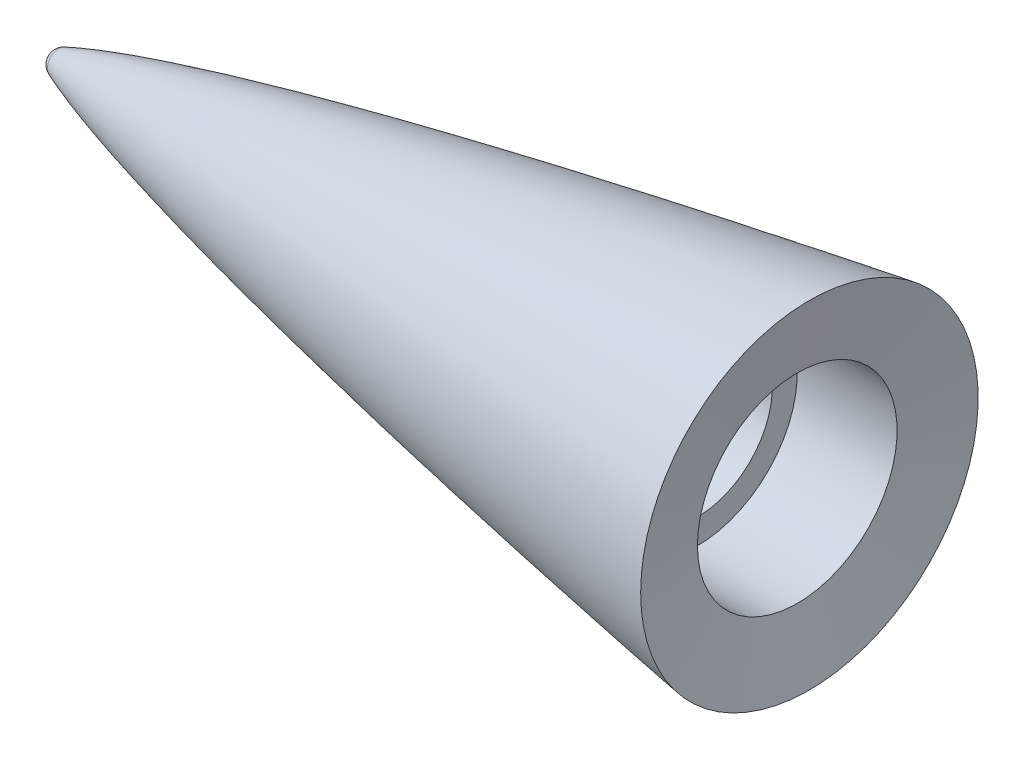
SolidWorks part; units mm, degrees
material "6061-T6 (SS)"
ref_plane "Front Plane" through (0, 0, 0) normal (0, 0, 1) x (1, 0, 0)
ref_plane "Top Plane" through (0, 0, 0) normal (0, 1, 0) x (1, 0, 0)
ref_plane "Right Plane" through (0, 0, 0) normal (1, 0, 0) x (0, 0, -1)
sketch "Sketch1" plane through (0, 0, 0) normal (0, 1, 0) x (1, 0, 0)
  line L0 (0, 0) -> (113.3431, 0) construction
  line L1 (1.6973, 0) -> (45.8194, 0)
  line L2 (83.9194, 12.7) -> (96.6194, 12.7)
  line L3 (96.6194, 12.7) -> (98.1654, 21.4679)
  line L4 (83.9194, 9.525) -> (58.5194, 9.525)
  line L5 (83.9194, 12.7) -> (82.8669, 18.9622) construction
  line L6 (58.5194, 9.525) -> (45.8194, 0)
  line L8 (83.9194, 12.7) -> (83.9194, 9.525)
  arc A0 (2.6821, 1.4686) -> (1.6973, 0) centre (3.2848, 0) ccw
  spline S0 degree 4 poles (0, 0) (0.0034, 0.0099) (0.0124, 0.0287) (0.036, 0.0594) (0.0734, 0.1004) (0.1241, 0.1478) (0.1961, 0.208) (0.3018, 0.2875) (0.4718, 0.4021) (0.7529, 0.5714) (1.2295, 0.826) (2.0659, 1.2203) (3.5324, 1.8251) (5.9654, 2.7008) (9.9595, 3.9615) (15.3529, 5.459) (21.8477, 7.0868) (29.0559, 8.7493) (36.2876, 10.3139) (43.5327, 11.8013) (50.7947, 13.2272) (58.0593, 14.5995) (64.4352, 15.7629) (69.8852, 16.7323) (74.4605, 17.5301) (78.0669, 18.1509) (81.7865, 18.7815) (85.3087, 19.3727) (89.1704, 20.0106) (92.4601, 20.5499) (97.1008, 21.2989) (100.2743, 21.8052) (104.805, 22.5216) (106.4979, 22.7829) (108.0668, 23.0282) knots 0 0 0 0 0 0.000378 0.000756 0.001385 0.00201 0.00288 0.004147 0.006163 0.009417 0.014733 0.02367 0.039565 0.066726 0.108156 0.174994 0.241832 0.30867 0.375509 0.442347 0.509185 0.576023 0.642862 0.676281 0.7097 0.743119 0.776538 0.809957 0.843376 0.876795 0.910214 0.955107 1 1 1 1 1 construction
  spline S1 degree 4 poles (2.6821, 1.4686) (2.9821, 1.5917) (3.9828, 1.987) (6.0755, 2.7356) (9.9593, 3.9614) (15.3526, 5.4589) (21.8473, 7.0867) (29.0554, 8.7492) (36.2869, 10.3137) (43.5319, 11.8011) (50.7938, 13.227) (58.0582, 14.5993) (64.434, 15.7626) (69.8839, 16.7321) (74.4591, 17.5298) (78.0654, 18.1507) (81.785, 18.7813) (85.3071, 19.3724) (89.1687, 20.0104) (92.4584, 20.5496) (95.6643, 21.067) (97.3334, 21.3349) (98.165, 21.4679) (98.1654, 21.4679) knots 0.027847 0.027847 0.027847 0.027847 0.027847 0.039565 0.066726 0.108156 0.174994 0.241832 0.30867 0.375509 0.442347 0.509185 0.576023 0.642862 0.676281 0.7097 0.743119 0.776538 0.809957 0.843376 0.876795 0.910214 0.910233 0.910233 0.910233 0.910233 0.910233
  dimension "D5" = 9.525
  dimension "D8" = 100
  dimension "D3" = 12.7
  dimension "D10" = 1.5875
  dimension "D2" = 12.7
  dimension "D4" = 25.4
  dimension "D6" = 12.7
  dimension "D7" = 6.35
revolve "Revolve2" add sketch "Sketch1" angle 360 about L0
